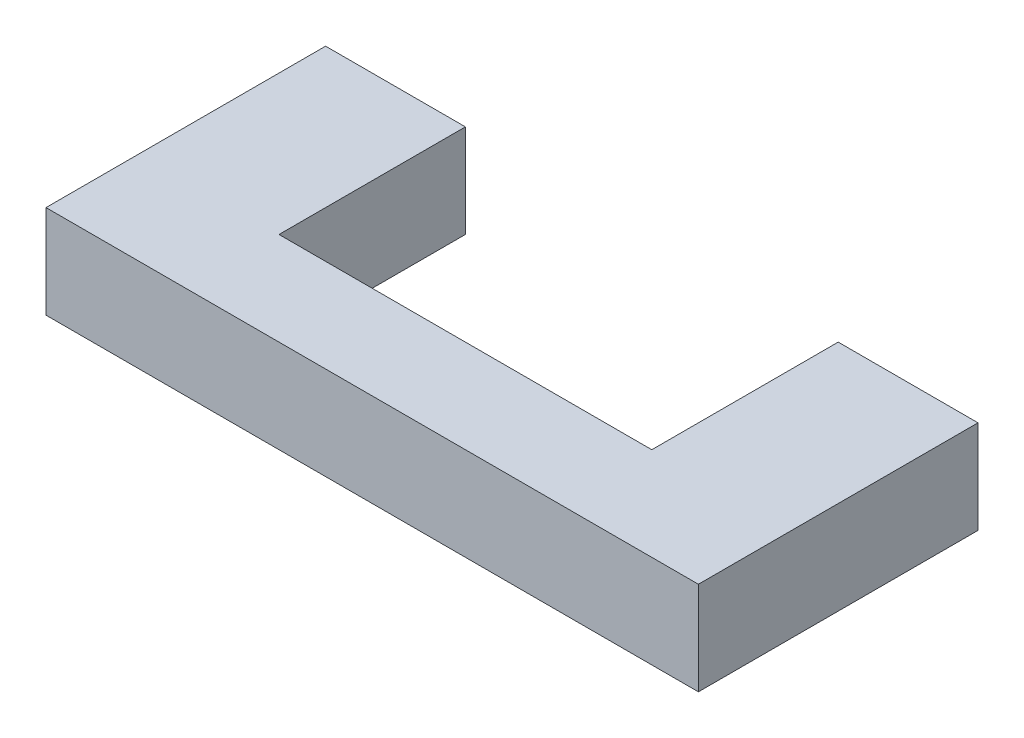
SolidWorks part; units mm, degrees
ref_plane "Front Plane" through (0, 0, 0) normal (0, 0, 1) x (1, 0, 0)
ref_plane "Top Plane" through (0, 0, 0) normal (0, 1, 0) x (1, 0, 0)
ref_plane "Right Plane" through (0, 0, 0) normal (1, 0, 0) x (0, 0, -1)
sketch "Sketch1" plane through (0, 0, 0) normal (0, 1, 0) x (1, 0, 0)
  line L1 (-22.225, -9.525) -> (22.225, -9.525)
  line L2 (-22.225, -9.525) -> (-22.225, 9.525)
  line L3 (-22.225, 9.525) -> (22.225, 9.525)
  line L4 (22.225, -9.525) -> (22.225, 9.525)
  line L5 (-22.225, -9.525) -> (22.225, 9.525) construction
  line L6 (-22.225, 9.525) -> (22.225, -9.525) construction
  point P0 (0, 0)
  dimension "D1" = 44.45
  dimension "D2" = 19.05
extrude "Boss-Extrude1" add sketch "Sketch1" along normal blind 6.35
sketch "Sketch2" plane through (0, 6.35, 0) normal (0, 1, 0) x (1, 0, 0)
  line L1 (22.225, 9.525) -> (-22.225, 9.525) construction
  line L2 (12.7, 9.525) -> (-12.7, 9.525)
  line L3 (12.7, 9.525) -> (12.7, -3.175)
  line L4 (12.7, -3.175) -> (-12.7, -3.175)
  line L5 (-12.7, 9.525) -> (-12.7, -3.175)
  line L6 (-22.225, 9.525) -> (-22.225, -9.525) construction
  dimension "D1" = 25.4
  dimension "D2" = 12.7
  dimension "D3" = 9.525
extrude "Cut-Extrude1" cut sketch "Sketch2" against normal up to surface (6.35 mm away) up to face at (0, 0, 0)
equation "\"screw-bed-layer-length\"= 1.75in'Clamp left-to-right is barely under."
equation "\"screw-bed-layer-width\"= .75in'Clamp top-to-bottom is just over."
equation "\"material-thickness\"= .25in"
equation "\"D1@Sketch1\" = \"screw-bed-layer-length\""
equation "\"D2@Sketch1\"=\"screw-bed-layer-width\""
equation "\"D1@Boss-Extrude1\"= \"material-thickness\""
equation "\"bus-bar-width\"= 1in"
equation "\"bus-bar-slot-depth\"= .5in"
equation "\"D1@Sketch2\"=\"bus-bar-width\""
equation "\"D2@Sketch2\"=\"bus-bar-slot-depth\""
equation "\"bus-bar-slot-edge-to-layer-edge\"= ( \"screw-bed-layer-length\" - \"bus-bar-width\" ) / 2"
equation "\"D3@Sketch2\"=\"bus-bar-slot-edge-to-layer-edge\""
